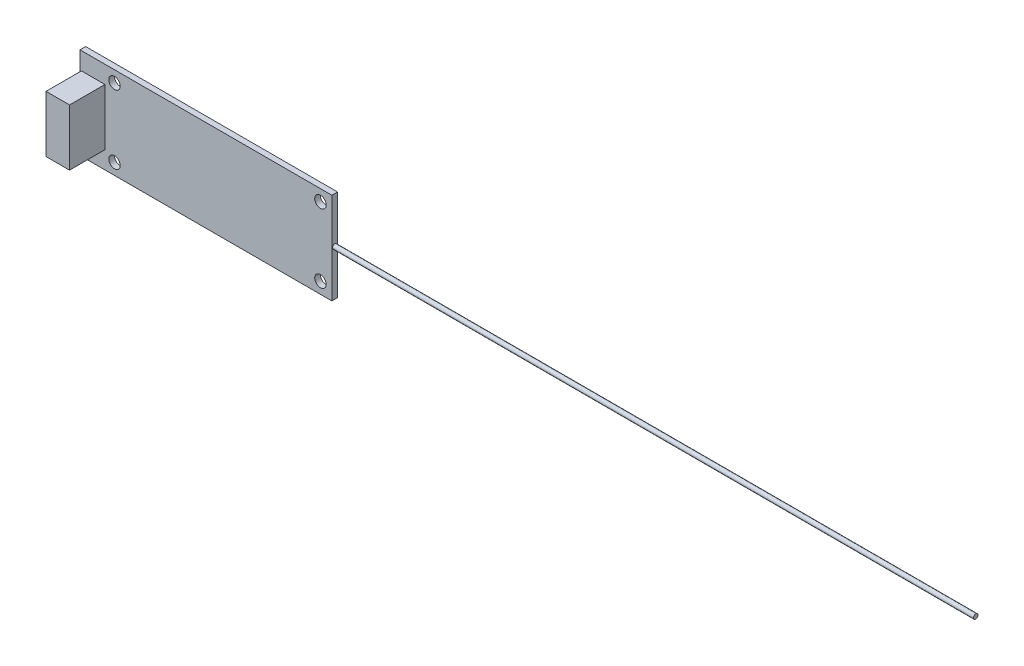
SolidWorks part; units mm, degrees
material "Printed Circuit Board"
ref_plane "Front Plane" through (0, 0, 0) normal (0, 0, 1) x (1, 0, 0)
ref_plane "Top Plane" through (0, 0, 0) normal (0, 1, 0) x (1, 0, 0)
ref_plane "Right Plane" through (0, 0, 0) normal (1, 0, 0) x (0, 0, -1)
sketch "Sketch1" plane through (0, 0, 0) normal (0, 0, 1) x (1, 0, 0)
  line L1 (-34.925, -12.7) -> (34.925, -12.7)
  line L2 (-34.925, -12.7) -> (-34.925, 12.7)
  line L3 (-34.925, 12.7) -> (34.925, 12.7)
  line L4 (34.925, -12.7) -> (34.925, 12.7)
  line L5 (-34.925, -12.7) -> (34.925, 12.7) construction
  line L6 (-34.925, 12.7) -> (34.925, -12.7) construction
  point P0 (0, 0)
  dimension "D1" = 69.85
  dimension "D2" = 25.4
extrude "Extrude1" add sketch "Sketch1" along normal blind 1.5748
sketch "Sketch2" plane through (0, 0, 1.5748) normal (0, 0, 1) x (1, 0, 0)
  line L0 (-34.925, 9.525) -> (-25.3822, 9.525) construction
  line L1 (-34.925, 12.7) -> (-34.925, -12.7) construction
  line L2 (-25.3822, 9.525) -> (31.75, 9.525) construction
  dimension "D1" = 9.5428
  dimension "D2" = 66.675
  dimension "D3" = 3.175
hole_wizard "1/8 (0.125) Diameter Hole1" positions "3DSketch1" profile "Sketch3" hole size "1/8" standard "Ansi Inch"
sketch3d "3DSketch1"
  point P0 (-25.3822, 9.525, 1.5748)
  point P3 (31.75, 9.525, 1.5748)
sketch "Sketch3" plane through (-25.3822, 9.525, 1.5748) normal (1, 0, 0) x (0, -1, 0)
  line L0 (0, 0) -> (0, 16.9559)
  line L1 (0, 16.9559) -> (1.5875, 16.002)
  line L2 (1.5875, 16.002) -> (1.5875, 0)
  line L5 (1.5875, 0) -> (0, 0)
  line L10 (0, 16.9559) -> (-1.5875, 16.002) construction
  line L11 (0, -6.35) -> (0, 107.95) construction
  dimension "Hole Dia." = 3.175
  dimension "Hole Depth" = 16.002
  dimension "Drill Angle" = 118
mirror "Mirror1" about plane through (0, 0, 0) normal (0, 1, 0) of "1/8 (0.125) Diameter Hole1"
sketch "Sketch4" plane through (34.925, 0, 0) normal (1, 0, 0) x (0, 0, -1)
  line L0 (0, 0) -> (-1.5441, 0) construction
  line L1 (0, -12.7) -> (0, 12.7) construction
  circle A0 centre (-0.772, 0) radius 0.635
  dimension "D1" = 1.27
extrude "Boss-Extrude1" add sketch "Sketch4" along normal blind 177.8
sketch "Sketch5" plane through (0, 0, 0) normal (0, 0, -1) x (-1, 0, 0)
  line L0 (34.925, -12.7) -> (-34.925, -12.7) construction
  line L1 (17.1361, -12.7) -> (9.0081, -12.7)
  line L2 (17.1361, -12.7) -> (17.1361, -3.9624)
  line L3 (17.1361, -3.9624) -> (9.0081, -3.9624)
  line L4 (9.0081, -12.7) -> (9.0081, -3.9624)
  dimension "D1" = 8.7376
  dimension "D2" = 8.128
extrude "USB Connector" add sketch "Sketch5" along normal blind 4.1402
sketch "Sketch6" plane through (0, -12.7, 0) normal (0, -1, 0) x (1, 0, 0)
  line L1 (-17.9544, 1.4835) -> (-7.548, 1.4835)
  line L2 (-17.9544, 1.4835) -> (-17.9544, -5.2984)
  line L3 (-17.9544, -5.2984) -> (-7.548, -5.2984)
  line L4 (-7.548, 1.4835) -> (-7.548, -5.2984)
  line L5 (-17.9544, 1.4835) -> (-7.548, -5.2984) construction
  line L6 (-17.9544, -5.2984) -> (-7.548, 1.4835) construction
  point P0 (-12.7512, -1.9075)
extrude "Charger" [suppressed] add sketch "Sketch6" along normal blind 20.828
sketch "Sketch7" [suppressed] plane through (0, -33.528, 0) normal (0, -1, 0) x (1, 0, 0)
  line L1 (-16.0158, 0) -> (-9.4301, 0)
  line L2 (-16.0158, 0) -> (-16.0158, -3.2572)
  line L3 (-16.0158, -3.2572) -> (-9.4301, -3.2572)
  line L4 (-9.4301, 0) -> (-9.4301, -3.2572)
  line L5 (-16.0158, 0) -> (-9.4301, -3.2572) construction
  line L6 (-16.0158, -3.2572) -> (-9.4301, 0) construction
  point P0 (-12.723, -1.6286)
extrude "Boss-Extrude2" [suppressed] add sketch "Sketch7" along normal blind 10.16
sketch "Sketch8" plane through (0, 0, 1.5748) normal (0, 0, 1) x (1, 0, 0)
  line L0 (0, 0) -> (-31.2801, 0) construction
  line L1 (-34.544, 7.8359) -> (-28.0162, 7.8359)
  line L2 (-34.544, 7.8359) -> (-34.544, -7.8359)
  line L3 (-34.544, -7.8359) -> (-28.0162, -7.8359)
  line L4 (-28.0162, 7.8359) -> (-28.0162, -7.8359)
  line L5 (-34.544, 7.8359) -> (-28.0162, -7.8359) construction
  line L6 (-34.544, -7.8359) -> (-28.0162, 7.8359) construction
  line L7 (-34.925, 12.7) -> (-34.925, -12.7) construction
  point P0 (-31.2801, 0)
  dimension "D1" = 6.5278
  dimension "D2" = 15.6718
  dimension "D3" = 0.381
extrude "Boss-Extrude3" add sketch "Sketch8" along normal blind 9.8298
